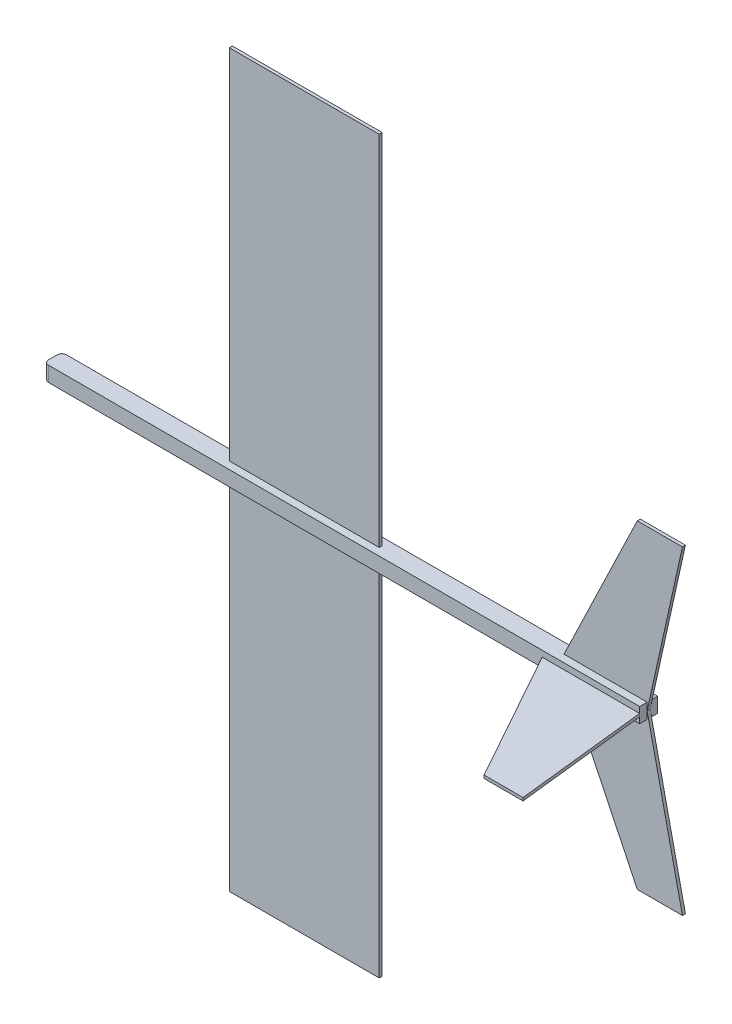
SolidWorks part; units mm, degrees
ref_plane "Front Plane" through (0, 0, 0) normal (0, 0, 1) x (1, 0, 0)
ref_plane "Top Plane" through (0, 0, 0) normal (0, 1, 0) x (1, 0, 0)
ref_plane "Right Plane" through (0, 0, 0) normal (1, 0, 0) x (0, 0, -1)
sketch "Sketch1" plane through (0, 0, 0) normal (0, 0, 1) x (1, 0, 0)
  line L0 (-159, 0) -> (159, 0) construction
  line L1 (159, 4) -> (-159, 4)
  line L2 (159, 4) -> (159, -4)
  line L3 (159, -4) -> (-159, -4)
  line L4 (-159, 4) -> (-159, -4)
  line L5 (159, 4) -> (-159, -4) construction
  line L6 (159, -4) -> (-159, 4) construction
  point P0 (0, 0)
  dimension "D1" = 8
  dimension "D2" = 318
extrude "Boss-Extrude1" add sketch "Sketch1" along normal mid plane 9.6
ref_plane "Plane3" through (0, 0, 0) normal (0, 0, 1) x (1, 0, 0)
sketch "Sketch3" plane through (0, 0, 0) normal (0, 0, 1) x (1, 0, 0)
  line L0 (-64, 0) -> (-64, 195)
  line L1 (-64, 195) -> (16, 195)
  line L2 (16, 195) -> (16, 0)
  line L3 (16, 0) -> (-64, 0)
  line L4 (-159, 4.2457) -> (-159, 3.7433) construction
  dimension "D1" = 95
  dimension "D2" = 80
  dimension "D3" = 80
  dimension "D4" = 195
  dimension "D5" = 90
extrude "Boss-Extrude2" add sketch "Sketch3" along normal mid plane 1.5875 contours L2 L3 L0 L1
mirror "Mirror1" about plane through (0, 0, 0) normal (0, 1, 0) of "Boss-Extrude2"
sketch "Sketch6" plane through (0, 0, 0) normal (0, 1, 0) x (1, 0, 0)
  line L0 (159, -4.8) -> (166.766, -74.8)
  line L1 (166.766, -74.8) -> (145.966, -74.8)
  line L2 (145.966, -74.8) -> (107, -4.8)
  line L3 (-159, -4.8) -> (159, -4.8) construction
  line L4 (107, -4.8) -> (159, -4.8)
  line L5 (151.166, -74.8) -> (120, -4.8) construction
  line L6 (159, -4.8) -> (-159, -4.8) construction
  dimension "D1" = 20.8
  dimension "D2" = 52
  dimension "D4" = 66
  dimension "D3" = 13
  dimension "D5" = 5.2
  dimension "D6" = 70
extrude "Boss-Extrude3" add sketch "Sketch6" along normal mid plane 1.5875 contours L0 L1 L2 L4
sketch "Sketch8" plane through (0, 0, 0) normal (0, 0, 1) x (1, 0, 0)
  line L0 (159, 0) -> (177.8349, 85.2)
  line L1 (5.28, 0) -> (-5.28, 0) construction
  line L2 (177.8349, 85.2) -> (153.7589, 85.2)
  line L3 (153.7589, 85.2) -> (112.7, 0)
  line L4 (112.7, 0) -> (159, 0)
  line L5 (159, -4) -> (159, -0.7937) construction
  dimension "D1" = 24.076
  dimension "D2" = 46.3
  dimension "D4" = 64.27
  dimension "D3" = 85.2
extrude "Boss-Extrude4" add sketch "Sketch8" along normal mid plane 1.5875 contours L0 L2 L3 L4
mirror "Mirror2" about plane through (0, 0, 0) normal (0, 1, 0) of "Boss-Extrude4"
fillet "Fillet1" radius 2.5 2 edges at (-159, 0, -4.8) (-159, 0, 4.8)
equation "\"Wing Root chord\"= 8cm"
equation "\"Taper Ratio\"= 0cm"
equation "\"Wing Tip chord\"= \"Wing Root chord\" * \"Taper Ratio\""
equation "\"D2@Sketch3\"=\"Wing Root chord\""
equation "\"Vertical Wing Root chord\"= 5.2"
equation "\"Vertical Wing Taper Ratio\"= 0.4"
equation "\"Vertical Wing Tip chord\"= \"Vertical Wing Root chord\" * \"Vertical Wing Taper Ratio\""
equation "\"D1@Sketch6\"=\"Vertical Wing Tip chord\""
equation "\"D2@Sketch6\"=\"Vertical Wing Root chord\""
equation "\"Stabilizer Root Chord\"= 4.63cm"
equation "\"Stabilizer Taper Ratio\"= 0.52'S"
equation "\"Stabilizer Tip chord\"= \"Stabilizer Root Chord\" * \"Stabilizer Taper Ratio\""
equation "\"D1@Sketch8\"=\"Stabilizer Tip chord\""
equation "\"D2@Sketch8\"=\"Stabilizer Root Chord\""
